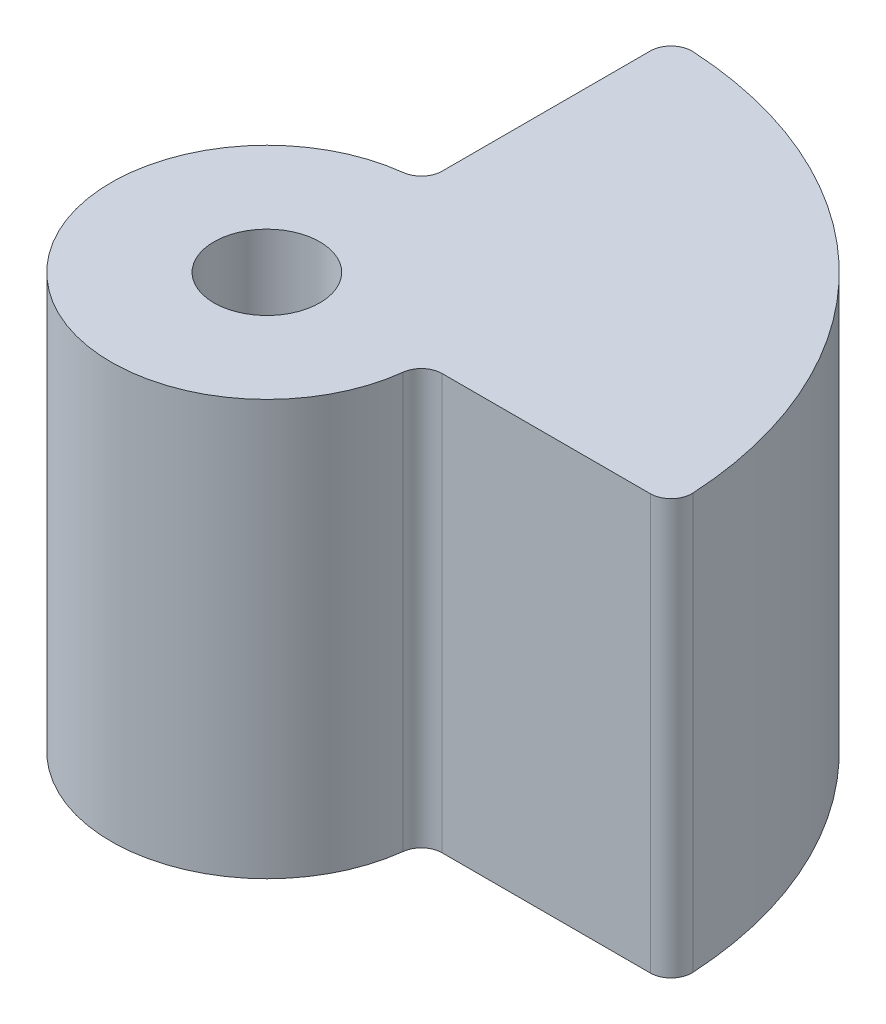
SolidWorks part; units mm, degrees
ref_plane "Front Plane" through (0, 0, 0) normal (0, 0, 1) x (1, 0, 0)
ref_plane "Top Plane" through (0, 0, 0) normal (0, 1, 0) x (1, 0, 0)
ref_plane "Right Plane" through (0, 0, 0) normal (1, 0, 0) x (0, 0, -1)
sketch "Sketch1" plane through (0, 0, 0) normal (0, 1, 0) x (1, 0, 0)
  line L0 (7.5, 0) -> (19.5, 0)
  line L1 (0, 7.5) -> (0, 19.5)
  arc A0 (19.5, 0) -> (0, 19.5) centre (0, 0) ccw
  arc A1 (0, 7.5) -> (7.5, 0) centre (0, 0) ccw
  dimension "D1" = 39
  dimension "D2" = 15
extrude "Boss-Extrude2" add sketch "Sketch1" along normal blind 20
sketch "Sketch2" plane through (0, 20, 0) normal (0, 1, 0) x (1, 0, 0)
  circle A0 centre (0, 0) radius 2.55
  dimension "D1" = 5.1
extrude "Cut-Extrude1" cut sketch "Sketch2" against normal blind 20
fillet "Fillet1" radius 1 4 edges at (0, 10, -19.5) (0, 10, -7.5) (7.5, 10, 0) (19.5, 10, 0)
